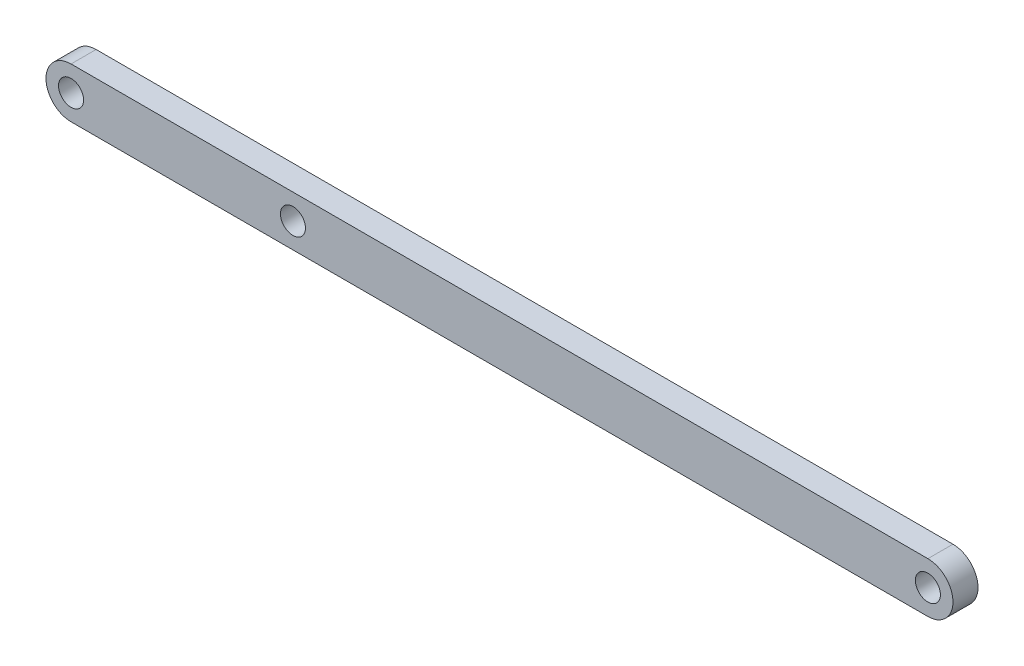
SolidWorks part; units mm, degrees
ref_plane "Plano frontal" through (0, 0, 0) normal (0, 0, 1) x (1, 0, 0)
ref_plane "Plano superior" through (0, 0, 0) normal (0, 1, 0) x (1, 0, 0)
ref_plane "Plano direito" through (0, 0, 0) normal (1, 0, 0) x (0, 0, -1)
sketch "Esboço1" plane through (0, 0, 0) normal (0, 0, 1) x (1, 0, 0)
  line L0 (-85.49, 5) -> (85.49, 5)
  line L2 (-85.49, -5) -> (85.49, -5)
  arc A0 (-85.49, 5) -> (-85.49, -5) centre (-85.49, 0) ccw
  arc A1 (85.49, 5) -> (85.49, -5) centre (85.49, 0) cw
  circle A2 centre (-85.49, 0) radius 2.5
  circle A3 centre (-41.21, 0) radius 2.5
  circle A4 centre (85.49, 0) radius 2.5
  point P3 (0, 5)
  dimension "D3" = 5
  dimension "D4" = 5
  dimension "D1" = 170.98
  dimension "D2" = 5
  dimension "D5" = 44.28
extrude "Ressalto-extrusão1" add sketch "Esboço1" along normal blind 5
